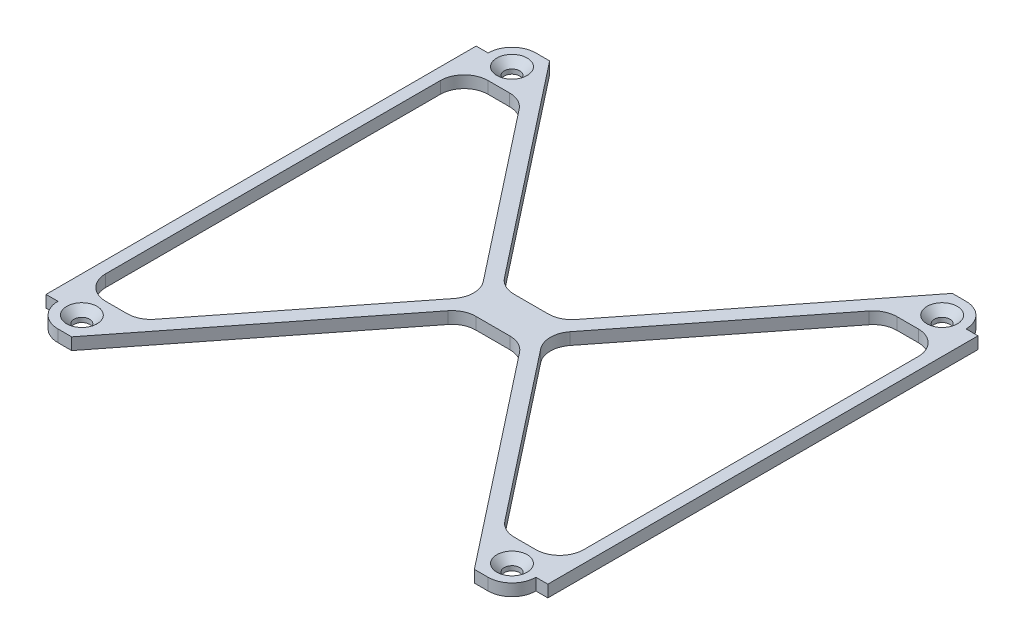
SolidWorks part; units mm, degrees
ref_plane "Front Plane" through (0, 0, 0) normal (0, 0, 1) x (1, 0, 0)
ref_plane "Top Plane" through (0, 0, 0) normal (0, 1, 0) x (1, 0, 0)
ref_plane "Right Plane" through (0, 0, 0) normal (1, 0, 0) x (0, 0, -1)
sketch "Sketch1" plane through (0, 0, 0) normal (0, 1, 0) x (1, 0, 0)
  line L989 (-45, 45) -> (45, 45) construction
  line L1008 (-52.5, -52.5) -> (52.5, -52.5) construction
  line L1009 (-52.5, -52.5) -> (-52.5, 52.5) construction
  line L1028 (-52.5, 52.5) -> (52.5, 52.5) construction
  line L1029 (52.5, -52.5) -> (52.5, 52.5) construction
  line L1030 (-52.5, -52.5) -> (52.5, 52.5) construction
  line L1031 (-52.5, 52.5) -> (52.5, -52.5) construction
  line L1032 (45, 45) -> (45, -45) construction
  line L1033 (45, -45) -> (-45, -45) construction
  line L1034 (-45, -45) -> (-45, 45) construction
  line L1035 (-52.5, 45) -> (-52.5, -45)
  line L1036 (-50, 45) -> (-52.5, 45)
  line L1037 (-50, 40) -> (-50, -40)
  line L1038 (-52.5, 0) -> (-50, 0) construction
  line L1039 (-45, 50) -> (-42.1272, 50)
  line L1040 (-42.1272, 50) -> (-6, 4)
  line L1041 (-6, 4) -> (6, 4)
  line L1042 (-38.088, 40) -> (-6.6731, 0)
  line L1043 (-32.12, 32.401) -> (-29.7607, 34.254) construction
  line L1044 (-50, 40) -> (-38.088, 40)
  line L1045 (-6.6731, 0) -> (0, 0) construction
  line L1046 (-55, 0) -> (55, 0) construction
  line L1047 (-50, -40) -> (-38.088, -40)
  line L1048 (-6, -4) -> (6, -4)
  line L1049 (-42.1272, -50) -> (-6, -4)
  line L1050 (-38.088, -40) -> (-6.6731, 0)
  line L1051 (-45, -50) -> (-42.1272, -50)
  line L1052 (-50, -45) -> (-52.5, -45)
  line L1053 (0, -55) -> (0, 55) construction
  line L1054 (45, -50) -> (42.1272, -50)
  line L1055 (50, -45) -> (52.5, -45)
  line L1056 (50, -40) -> (38.088, -40)
  line L1057 (38.088, -40) -> (6.6731, 0)
  line L1058 (42.1272, -50) -> (6, -4)
  line L1059 (38.088, 40) -> (6.6731, 0)
  line L1060 (42.1272, 50) -> (6, 4)
  line L1061 (45, 50) -> (42.1272, 50)
  line L1062 (50, 45) -> (52.5, 45)
  line L1063 (50, 40) -> (38.088, 40)
  line L1064 (50, 40) -> (50, -40)
  line L1065 (52.5, 45) -> (52.5, -45)
  circle A0 centre (-45, 45) radius 1.625
  circle A1 centre (45, 45) radius 1.625
  circle A2 centre (-45, -45) radius 1.625
  circle A3 centre (45, -45) radius 1.625
  arc A4 (-45, 50) -> (-50, 45) centre (-45, 45) ccw
  arc A8 (-45, -50) -> (-50, -45) centre (-45, -45) cw
  arc A9 (45, -50) -> (50, -45) centre (45, -45) ccw
  arc A10 (45, 50) -> (50, 45) centre (45, 45) cw
  point P0 (0, 0)
  point P18 (-45, 49.6121)
  dimension "D5" = 2.5
  dimension "D6" = 3
  dimension "D8" = 12
  dimension "D7" = 5
  dimension "D2" = 90
  dimension "D3" = 3.25
  dimension "D4" = 5
  dimension "D1" = 105
  dimension "D9" = 8
extrude "Boss-Extrude1" add sketch "Sketch1" along normal blind 2.5
fillet "Fillet1" radius 5 6 edges at (6, 1.25, 4) (-6, 1.25, 4) (6, 1.25, -4) (-6, 1.25, -4) (6.6731, 1.25, 0) (-6.6731, 1.25, 0)
fillet "Fillet2" radius 5 8 edges at (50, 1.25, -40) (38.088, 1.25, -40) (38.088, 1.25, 40) (50, 1.25, 40) (-38.088, 1.25, 40) (-50, 1.25, 40) (-38.088, 1.25, -40) (-50, 1.25, -40)
chamfer "Chamfer1" distance 1.55 angle 45 4 edges at (-45, 2.5, 46.625) (45, 2.5, 46.625) (45, 2.5, -43.375) (-45, 2.5, -43.375)
